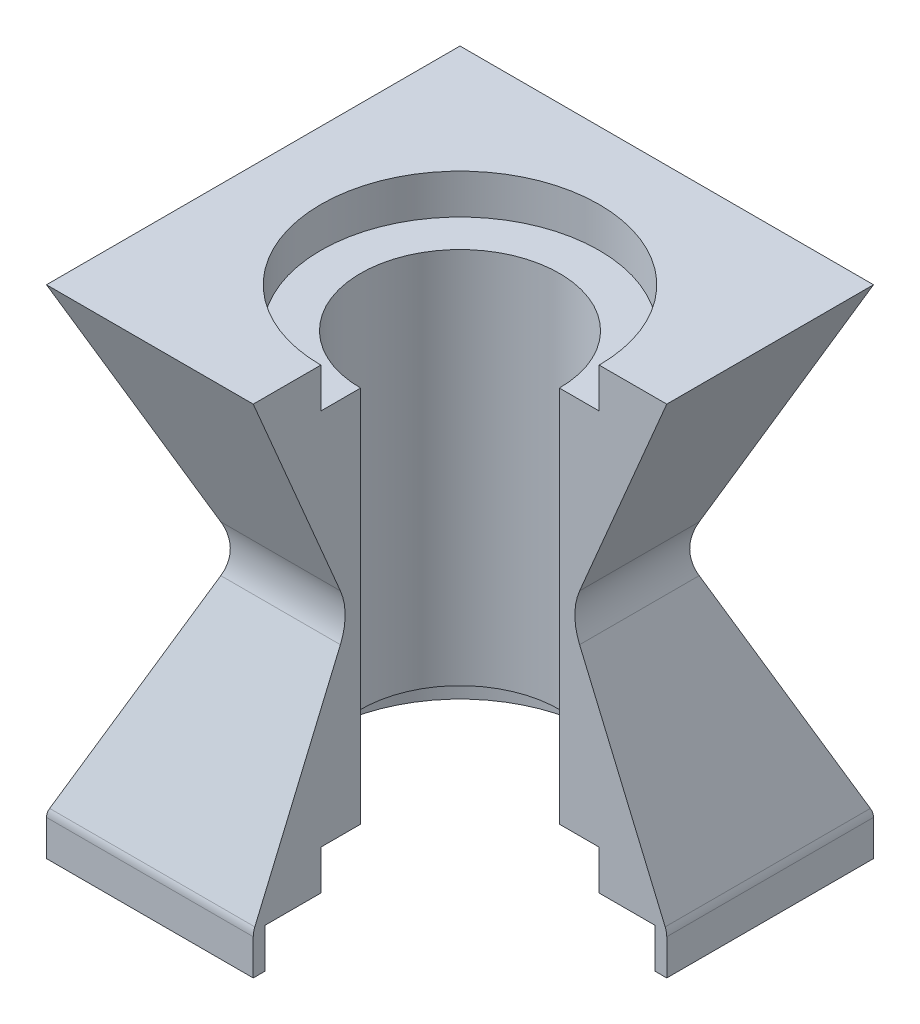
SolidWorks part; units mm, degrees
material "Cast Stainless Steel"
ref_plane "Front Plane" through (0, 0, 0) normal (0, 0, 1) x (1, 0, 0)
ref_plane "Top Plane" through (0, 0, 0) normal (0, 1, 0) x (1, 0, 0)
ref_plane "Right Plane" through (0, 0, 0) normal (1, 0, 0) x (0, 0, -1)
sketch "Sketch1" plane through (0, 0, 0) normal (0, 1, 0) x (1, 0, 0)
  line L0 (0, 0) -> (0, 104)
  line L1 (0, 104) -> (104, 104)
  line L2 (104, 104) -> (104, 0)
  line L3 (104, 0) -> (0, 0)
  line L4 (52, 104) -> (52, 0) construction
  line L5 (52, 0) -> (52, 52) construction
  line L6 (52, 52) -> (104, 52) construction
  line L7 (104, 52) -> (0, 52) construction
  circle A0 centre (52, 52) radius 25
  dimension "D2" = 50
  dimension "D3" = 50
  dimension "D1" = 104
extrude "Boss-Extrude2" add sketch "Sketch1" along normal blind 115
sketch "Sketch4" plane through (104, 0, 0) normal (1, 0, 0) x (0, 0, -1)
  line L0 (52, 115) -> (52, 0) construction
  line L1 (0, 115) -> (104, 115) construction
  line L2 (0, 0) -> (104, 0) construction
  line L3 (0, 115) -> (0, 0)
  line L4 (104, 0) -> (79.5927, 57.5)
  line L5 (104, 115) -> (104, 0)
  line L6 (0, 0) -> (24.4073, 57.5)
  line L7 (24.4073, 57.5) -> (0, 115)
  line L8 (79.5927, 57.5) -> (104, 115)
  dimension "D1" = 23
  dimension "D2" = 23
sketch "Sketch5" plane through (0, 0, -104) normal (0, 0, -1) x (-1, 0, 0)
  line L0 (-52, 115) -> (-52, 0) construction
  line L1 (-104, 115) -> (0, 115) construction
  line L2 (-104, 0) -> (0, 0) construction
  line L3 (-104, 115) -> (-104, 0)
  line L4 (-104, 0) -> (-79.5927, 57.5)
  line L5 (-79.5927, 57.5) -> (-104, 115)
  line L6 (0, 0) -> (-24.4073, 57.5)
  line L7 (0, 115) -> (0, 0)
  line L8 (-24.4073, 57.5) -> (0, 115)
  dimension "D1" = 23
  dimension "D2" = 23
extrude "Cut-Extrude3" cut sketch "Sketch5" against normal blind 115
extrude "Cut-Extrude4" cut sketch "Sketch4" against normal blind 115
fillet "Fillet1" radius 15 4 edges at (52, 57.5, -79.5927) (79.5927, 57.5, -52) (52, 57.5, -24.4073) (24.4073, 57.5, -52)
sketch "Sketch7" plane through (0, 115, 0) normal (0, 1, 0) x (1, 0, 0)
  line L0 (52, -27.1235) -> (52, 52)
  line L1 (52, 52) -> (131.1235, 52)
  circle A0 centre (52, 52) radius 35
  arc A1 (131.1235, 52) -> (52, -27.1235) centre (52, 52) cw
  dimension "D1" = 70
extrude "Cut-Extrude7" cut sketch "Sketch7" against normal blind 10 contours A0
sketch "Sketch8" plane through (0, 115, 0) normal (0, 1, 0) x (1, 0, 0)
  line L0 (52, 87) -> (52, 17) construction
  line L1 (52, -33.4562) -> (52, 52)
  line L2 (52, 52) -> (137.4562, 52)
  circle A0 centre (52, 52) radius 35 construction
  circle A1 centre (52, 52) radius 35 construction
  arc A2 (137.4562, 52) -> (52, -33.4562) centre (52, 52) cw
extrude "Cut-Extrude8" cut sketch "Sketch8" against normal blind 10000
sketch "Sketch9" plane through (0, 0, 0) normal (0, -1, 0) x (-1, 0, 0)
  line L0 (-52, 27) -> (-52, 77) construction
  arc A0 (-52, 27) -> (-77, 52) centre (-52, 52) ccw construction
  circle A1 centre (-52, 52) radius 35
  dimension "D1" = 70
extrude "Cut-Extrude9" cut sketch "Sketch9" against normal blind 10
sketch "Sketch10" plane through (0, 0, 0) normal (0, -1, 0) x (-1, 0, 0)
  line L0 (-104, 52) -> (-104, 104)
  line L1 (-104, 104) -> (0, 104)
  line L2 (0, 104) -> (0, 0)
  line L3 (0, 0) -> (-52, 0)
  line L4 (-101, 52) -> (-101, 101)
  line L5 (-101, 101) -> (-3, 101)
  line L6 (-3, 101) -> (-3, 3)
  line L7 (-3, 3) -> (-52, 3)
  line L8 (-52, 3) -> (-52, 0)
  line L9 (-101, 52) -> (-104, 52)
  dimension "D1" = 3
extrude "Boss-Extrude3" add sketch "Sketch10" along normal blind 10
sketch "Sketch11" plane through (0, 0, 0) normal (0, -1, 0) x (-1, 0, 0)
  line L0 (-3, 3) -> (-101, 101) construction
  line L1 (-101, 101) -> (-3, 101) construction
  line L2 (-3, 101) -> (-52, 52) construction
  line L3 (-21.948, 21.948) -> (-11.3414, 11.3414) construction
  line L4 (-19.8266, 24.0693) -> (-9.22, 13.4627)
  line L5 (-24.0693, 19.8266) -> (-13.4627, 9.22)
  line L9 (-79.9307, 84.1734) -> (-90.5373, 94.78)
  line L10 (-84.1734, 79.9307) -> (-94.78, 90.5373)
  line L11 (-82.052, 82.052) -> (-92.6586, 92.6586) construction
  line L12 (-19.8266, 79.9307) -> (-9.22, 90.5373)
  line L13 (-24.0693, 84.1734) -> (-13.4627, 94.78)
  line L14 (-21.948, 82.052) -> (-11.3414, 92.6586) construction
  line L15 (-79.9307, 19.8266) -> (-90.5373, 9.22) [skipped]
  line L16 (-84.1734, 24.0693) -> (-94.78, 13.4627) [skipped]
  arc A0 (-19.8266, 24.0693) -> (-24.0693, 19.8266) centre (-21.948, 21.948) ccw
  arc A1 (-13.4627, 9.22) -> (-9.22, 13.4627) centre (-11.3414, 11.3414) ccw
  arc A4 (-84.1734, 79.9307) -> (-79.9307, 84.1734) centre (-82.052, 82.052) ccw
  arc A5 (-90.5373, 94.78) -> (-94.78, 90.5373) centre (-92.6586, 92.6586) ccw
  arc A6 (-24.0693, 84.1734) -> (-19.8266, 79.9307) centre (-21.948, 82.052) ccw
  arc A7 (-9.22, 90.5373) -> (-13.4627, 94.78) centre (-11.3414, 92.6586) ccw
  arc A8 (-79.9307, 19.8266) -> (-84.1734, 24.0693) centre (-82.052, 21.948) ccw [skipped]
  arc A9 (-94.78, 13.4627) -> (-90.5373, 9.22) centre (-92.6586, 11.3414) ccw [skipped]
  point P10 (-16.6447, 16.6447)
  point P27 (-87.3553, 87.3553)
  point P34 (-16.6447, 87.3553)
  dimension "D2" = 3
  dimension "D1" = 15
  dimension "D4" = 4
extrude "Cut-Extrude10" cut sketch "Sketch11" against normal blind 10
fillet "Fillet2" radius 5 4 edges at (26, 0, 0) (0, 0, -52) (52, 0, -104) (104, 0, -78)
equation "\"A\"=75"
equation "\"B\"= 104"
equation "\"C\"= 23"
equation "\"D1@Sketch4\"=\"C\""
equation "\"D2@Sketch4\"=\"C\""
equation "\"D1@Sketch5\"=\"C\""
equation "\"D2@Sketch5\"=\"C\""
